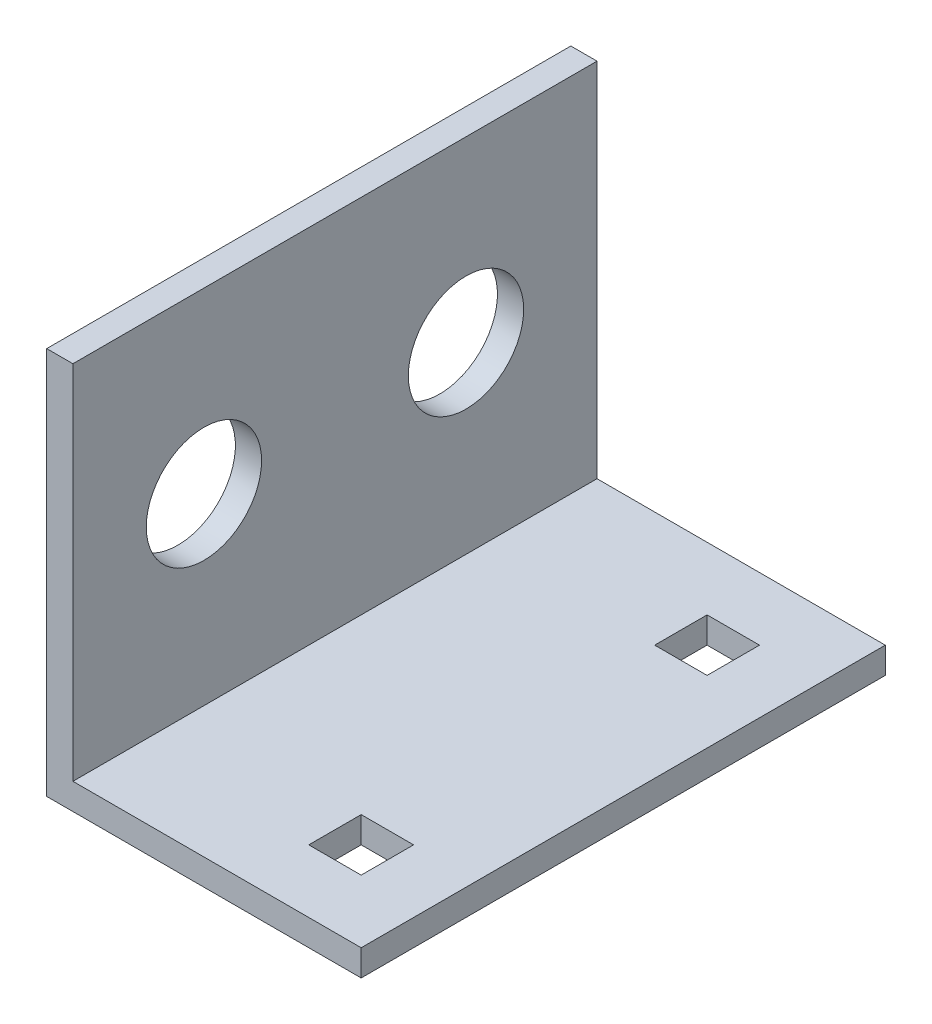
SolidWorks part; units mm, degrees
material "ABS"
ref_plane "Front Plane" through (0, 0, 0) normal (0, 0, 1) x (1, 0, 0)
ref_plane "Top Plane" through (0, 0, 0) normal (0, 1, 0) x (1, 0, 0)
ref_plane "Right Plane" through (0, 0, 0) normal (1, 0, 0) x (0, 0, -1)
sketch "Sketch1" plane through (0, 0, 0) normal (0, 0, 1) x (1, 0, 0)
  line L1 (0, 0) -> (4.8052, 0)
  line L2 (0, 0) -> (0, 37)
  line L3 (0, 37) -> (2.5, 37)
  line L4 (2.5, 2.5) -> (2.5, 37)
  line L5 (0, 0) -> (30, 0)
  line L6 (0, 0) -> (0, 4.8052)
  line L7 (2.5, 2.5) -> (30, 2.5)
  line L8 (30, 0) -> (30, 2.5)
  dimension "D1" = 37
  dimension "D2" = 30
  dimension "D3" = 2.5
  dimension "D4" = 2.5
extrude "Boss-Extrude1" add sketch "Sketch1" against normal blind 50 contours L5 L8 L7 L4 L3 L2 L1
sketch "Sketch2" plane through (0, 0, 0) normal (-1, 0, 0) x (0, 0, 1)
  line L0 (-50, 0) -> (-50, 37) construction
  line L1 (0, 0) -> (0, 37) construction
  line L2 (-50, 0) -> (0, 0) construction
  circle A0 centre (-37.5, 20) radius 5.5
  circle A1 centre (-12.5, 20) radius 5.5
  dimension "D3" = 11
  dimension "D4" = 11
  dimension "D1" = 12.5
  dimension "D2" = 12.5
  dimension "D5" = 20
  dimension "D6" = 20
extrude "Cut-Extrude1" cut sketch "Sketch2" against normal through all
sketch "Sketch3" plane through (0, 0, 0) normal (0, -1, 0) x (1, 0, 0)
  line L0 (30, -50) -> (30, 0) construction
  line L1 (24, -6) -> (19, -6)
  line L2 (24, -6) -> (24, -11)
  line L3 (24, -11) -> (19, -11)
  line L4 (19, -6) -> (19, -11)
  line L5 (24, -44) -> (19, -44)
  line L6 (24, -44) -> (24, -39)
  line L7 (24, -39) -> (19, -39)
  line L8 (19, -44) -> (19, -39)
  line L9 (0, 0) -> (30, 0) construction
  line L10 (0, -50) -> (30, -50) construction
  dimension "D1" = 6
  dimension "D2" = 6
  dimension "D3" = 5
  dimension "D4" = 5
  dimension "D5" = 5
  dimension "D6" = 5
  dimension "D7" = 6
  dimension "D8" = 6
extrude "Cut-Extrude2" cut sketch "Sketch3" against normal blind 50
